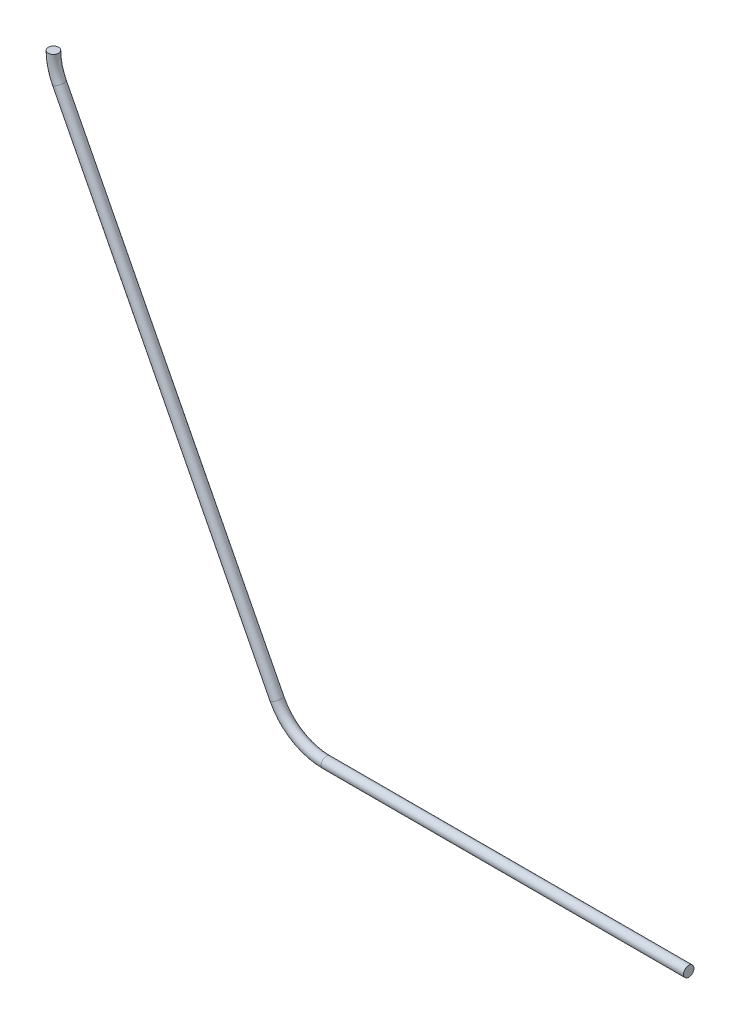
SolidWorks part; units mm, degrees
ref_plane "prox_pulley" through (0, 0, 0) normal (0, 0, 1) x (1, 0, 0)
ref_plane "Top Plane" through (0, 0, 0) normal (0, 1, 0) x (1, 0, 0)
ref_plane "Right Plane" through (0, 0, 0) normal (1, 0, 0) x (0, 0, -1)
sketch "Sketch1" plane through (0, 0, 0) normal (0, 0, 1) x (1, 0, 0)
  line L2 (-4.7706, -2.4435) -> (16.2294, -43.4435)
  line L3 (21, -46.36) -> (56, -46.36)
  circle A0 centre (0, 0) radius 5.36 construction
  arc A1 (-5.36, 0) -> (-4.7706, -2.4435) centre (0, 0) ccw
  circle A2 centre (21, -41) radius 5.36 construction
  arc A3 (16.2294, -43.4435) -> (21, -46.36) centre (21, -41) ccw
  dimension "D1" = 10.72
  dimension "D2" = 35
  dimension "D3" = 21
  dimension "D4" = 41
ref_point "tendon_start"
sketch "Sketch6" plane through (0, 0, 0) normal (0, 1, 0) x (1, 0, 0)
  circle A0 centre (-5.36, 0) radius 0.5
  dimension "D1" = 1
sweep "Sweep1" add profiles "Sketch6" path "Sketch1"
